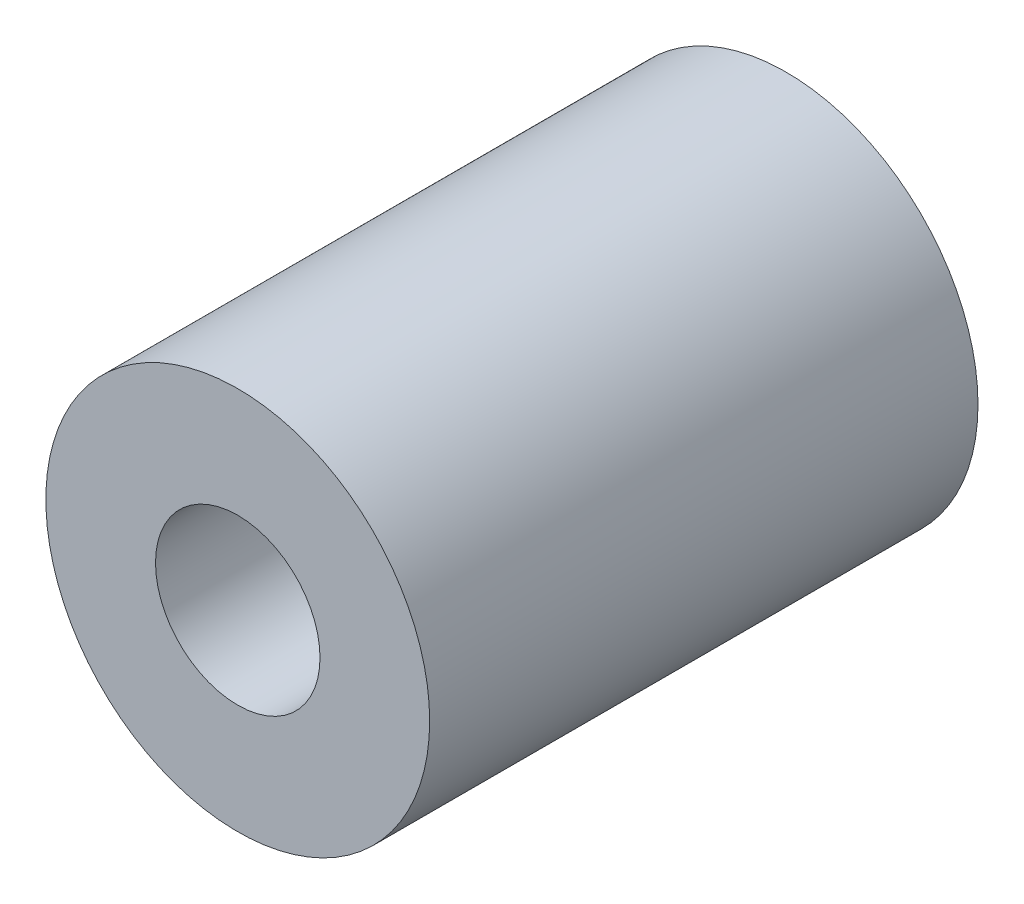
SolidWorks part; units mm, degrees
ref_plane "前视基准面" through (0, 0, 0) normal (0, 0, 1) x (1, 0, 0)
ref_plane "上视基准面" through (0, 0, 0) normal (0, 1, 0) x (1, 0, 0)
ref_plane "右视基准面" through (0, 0, 0) normal (1, 0, 0) x (0, 0, -1)
sketch "草图1" plane through (0, 0, 0) normal (0, 0, 1) x (1, 0, 0)
  circle A0 centre (0, 0) radius 1.5
  circle A1 centre (0, 0) radius 3.5
  dimension "D1" = 3
  dimension "D2" = 7
extrude "凸台-拉伸1" add sketch "草图1" along normal blind 10
